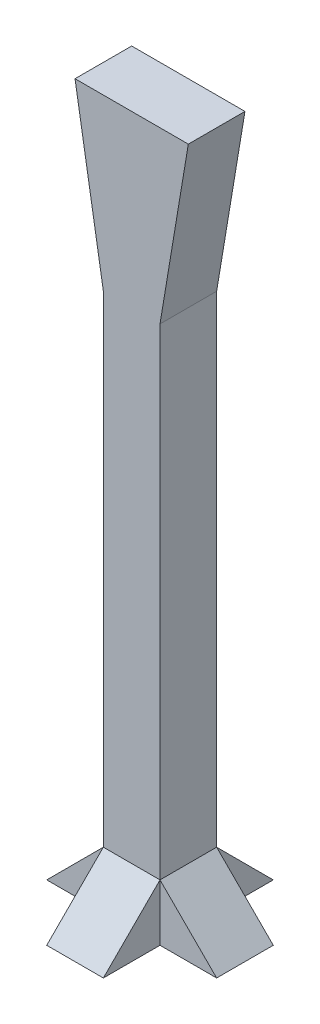
SolidWorks part; units mm, degrees
ref_plane "Front" through (0, 0, 0) normal (0, 0, 1) x (1, 0, 0)
ref_plane "Top" through (0, 0, 0) normal (0, 1, 0) x (1, 0, 0)
ref_plane "Right" through (0, 0, 0) normal (1, 0, 0) x (0, 0, -1)
sketch "Sketch1" plane through (0, 0, 0) normal (0, 0, 1) x (1, 0, 0)
  line L1 (-10, -125) -> (10, -125)
  line L2 (-10, -125) -> (-10, 125)
  line L3 (-10, 125) -> (10, 125)
  line L4 (10, -125) -> (10, 125)
  line L5 (-10, -125) -> (10, 125) construction
  line L6 (-10, 125) -> (10, -125) construction
  point P0 (0, 0)
  dimension "D1" = 20
  dimension "D2" = 250
extrude "Boss-Extrude1" add sketch "Sketch1" along normal blind 20
sketch "Sketch2" plane through (0, 0, 20) normal (0, 0, 1) x (1, 0, 0)
  line L0 (10, -125) -> (10, -105)
  line L1 (10, -125) -> (10, 125) construction
  line L2 (10, -105) -> (30, -125)
  line L3 (30, -125) -> (10, -125)
  dimension "D1" = 20
  dimension "D2" = 20
extrude "Boss-Extrude2" add sketch "Sketch2" against normal up to surface (20 mm away) up to face at (0, 0, 0)
mirror "Mirror2" about plane through (0, 0, 0) normal (1, 0, 0) of "Boss-Extrude2"
sketch "Sketch3" plane through (10, 0, 0) normal (1, 0, 0) x (0, 0, -1)
  line L0 (-20, -105) -> (-20, -125)
  line L1 (-20, -125) -> (-40, -125)
  line L2 (-40, -125) -> (-20, -105)
  dimension "D1" = 20
extrude "Boss-Extrude3" add sketch "Sketch3" against normal up to surface (20 mm away) up to face at (-10, 10, 10)
ref_plane "Plane1" through (0, 0, 10) normal (0, 0, -1) x (-1, 0, 0)
mirror "Mirror3" about plane through (0, 0, 10) normal (0, 0, -1) of "Boss-Extrude3"
sketch "Sketch4" plane through (0, 0, 20) normal (0, 0, 1) x (1, 0, 0)
  line L0 (-10, 125) -> (-20, 125)
  line L1 (-20, 125) -> (-10, 65)
  line L2 (-10, 125) -> (-10, -105) construction
  line L3 (-10, 125) -> (-10, 65)
  dimension "D1" = 10
  dimension "D2" = 60
extrude "Boss-Extrude4" add sketch "Sketch4" against normal up to surface (20 mm away) up to face at (0, 10, 0)
mirror "Mirror4" about plane through (0, 0, 0) normal (1, 0, 0) of "Boss-Extrude4"
